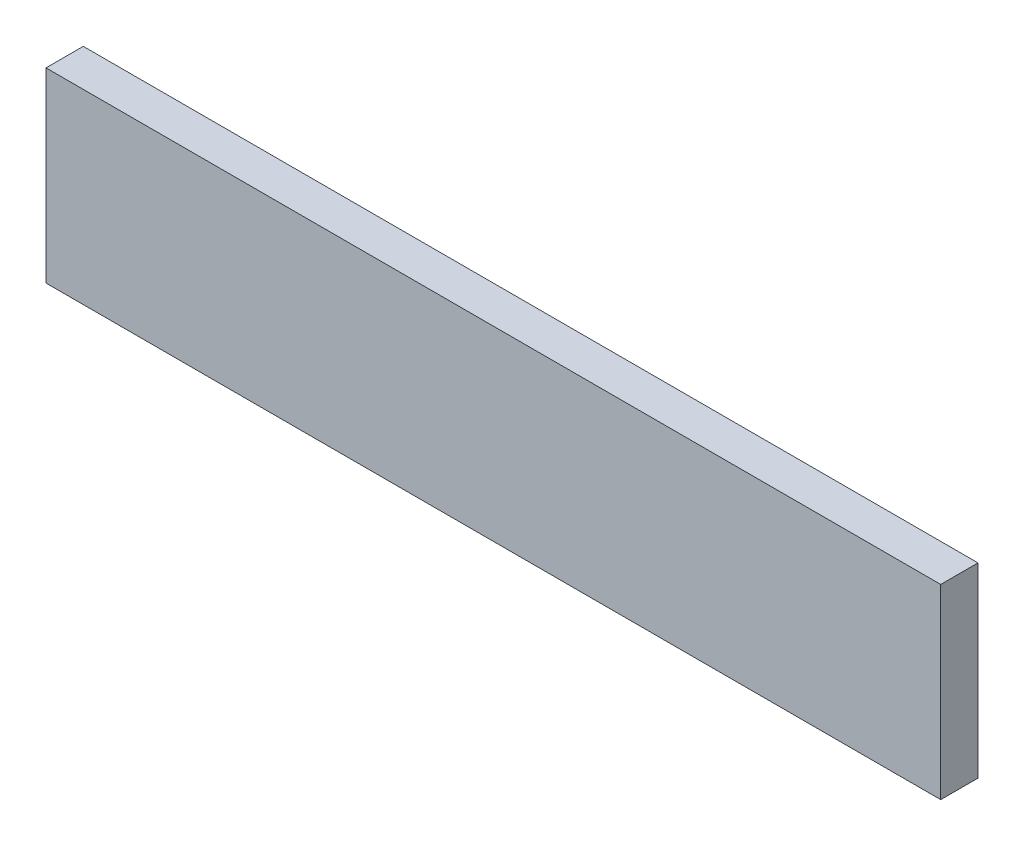
SolidWorks part; units mm, degrees
ref_plane "Front Plane" through (0, 0, 0) normal (0, 0, 1) x (1, 0, 0)
ref_plane "Top Plane" through (0, 0, 0) normal (0, 1, 0) x (1, 0, 0)
ref_plane "Right Plane" through (0, 0, 0) normal (1, 0, 0) x (0, 0, -1)
sketch "Sketch1" plane through (0, 0, 0) normal (0, 0, 1) x (1, 0, 0)
  line L1 (-76.2, -15.875) -> (76.2, -15.875)
  line L2 (-76.2, -15.875) -> (-76.2, 15.875)
  line L3 (-76.2, 15.875) -> (76.2, 15.875)
  line L4 (76.2, -15.875) -> (76.2, 15.875)
  line L5 (-76.2, -15.875) -> (76.2, 15.875) construction
  line L6 (-76.2, 15.875) -> (76.2, -15.875) construction
  point P0 (0, 0)
  dimension "D1" = 152.4
  dimension "D2" = 31.75
extrude "Boss-Extrude1" add sketch "Sketch1" against normal blind 6.35
